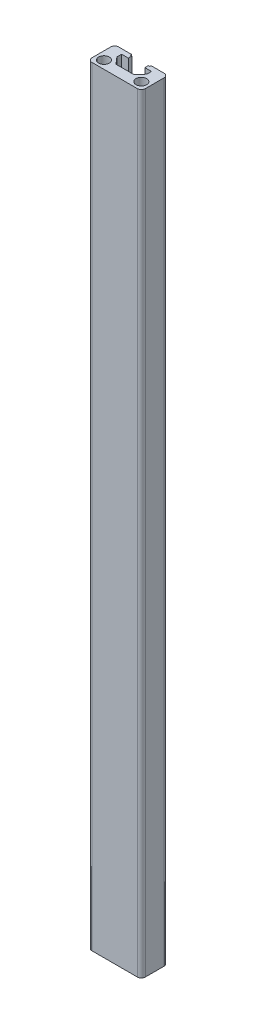
SolidWorks part; units mm, degrees
ref_plane "前视基准面" through (0, 0, 0) normal (0, 0, 1) x (1, 0, 0)
ref_plane "上视基准面" through (0, 0, 0) normal (0, 1, 0) x (1, 0, 0)
ref_plane "右视基准面" through (0, 0, 0) normal (1, 0, 0) x (0, 0, -1)
sketch "草图1" plane through (0, 0, 0) normal (0, 1, 0) x (1, 0, 0)
  line L0 (0, 0) -> (20, 0)
  line L1 (20, 0) -> (20, 10)
  line L2 (20, 10) -> (13.65, 10)
  line L3 (0, 10) -> (0, 0)
  line L4 (6.35, 10) -> (6.35, 9.5104)
  line L5 (6.35, 9.5104) -> (6.9, 9.5104)
  line L6 (6.9, 9.5104) -> (6.9, 8.2)
  line L7 (6.9, 8.2) -> (4.4, 8.2)
  line L8 (4.4, 8.2) -> (4.4, 6.4475)
  line L9 (4.4, 6.4475) -> (6.5873, 3.9)
  line L11 (15.6, 6.4475) -> (15.6, 8.2)
  line L12 (15.6, 8.2) -> (13.1, 8.2)
  line L13 (13.1, 8.2) -> (13.1, 9.5104)
  line L14 (13.1, 9.5104) -> (13.65, 9.5104)
  line L15 (13.65, 9.5104) -> (13.65, 10)
  line L16 (6.35, 10) -> (0, 10)
  line L17 (10, 0) -> (10, 13.7687) construction
  line L18 (6.5873, 3.9) -> (13.4127, 3.9)
  line L19 (13.4127, 3.9) -> (15.6, 6.4475)
  circle A0 centre (3, 3) radius 2
  circle A1 centre (17, 3) radius 2
  point P12 (10, 3.9)
  dimension "D8" = 4
  dimension "D1" = 20
  dimension "D2" = 10
  dimension "D3" = 7.3
  dimension "D4" = 6.2
  dimension "D5" = 1.8
  dimension "D6" = 4.3
  dimension "D7" = 11.2
  dimension "D9" = 3
  dimension "D10" = 14
extrude "凸台-拉伸1" add sketch "草图1" along normal blind 288
fillet "圆角1" radius 1.5 4 edges at (0, 144, -10) (0, 144, 0) (20, 144, -10) (20, 144, 0)
